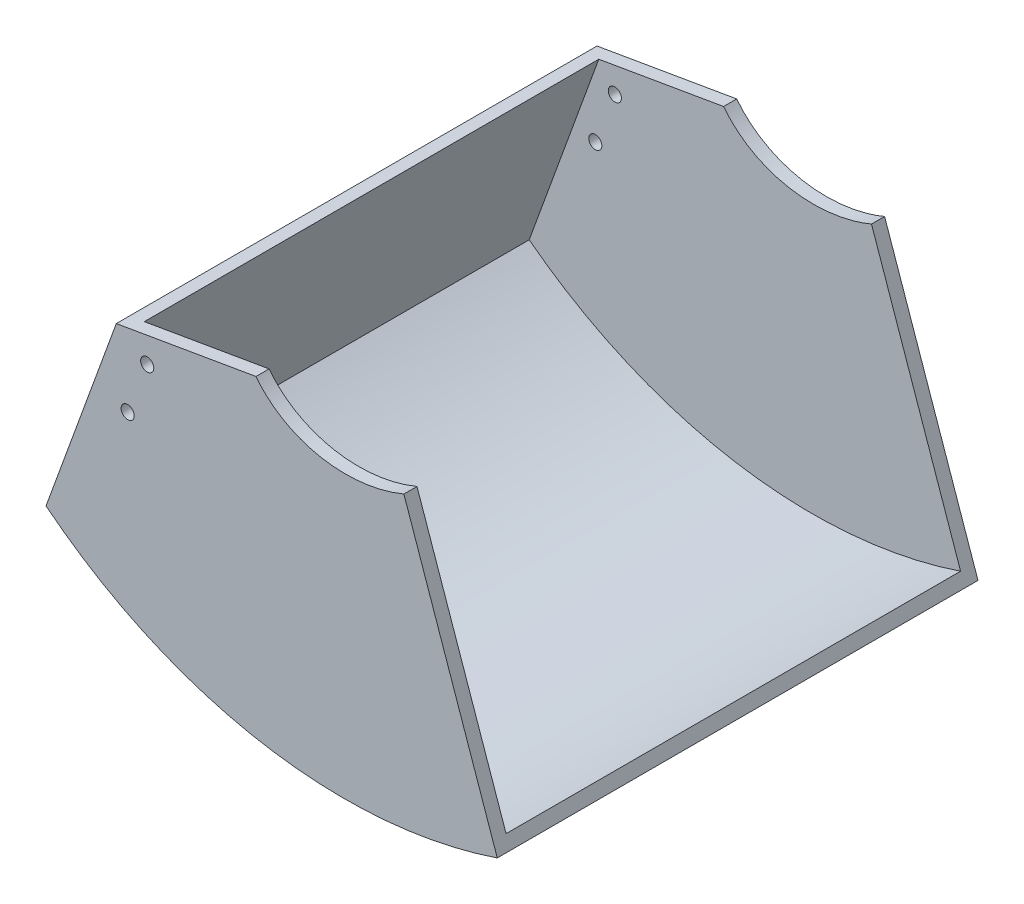
SolidWorks part; units mm, degrees
ref_plane "前视基准面" through (0, 0, 0) normal (0, 0, 1) x (1, 0, 0)
ref_plane "上视基准面" through (0, 0, 0) normal (0, 1, 0) x (1, 0, 0)
ref_plane "右视基准面" through (0, 0, 0) normal (1, 0, 0) x (0, 0, -1)
ref_plane "基准面4" through (0, 0, 110) normal (0, 0, 1) x (1, 0, 0)
sketch "草图1" plane through (0, 0, 110) normal (0, 0, 1) x (1, 0, 0)
  line L0 (48.0437, 49.6866) -> (16.0836, 44.1894)
  line L1 (16.0836, 44.1894) -> (0, 0)
  line L2 (103.2604, -18.1269) -> (81.8905, 43.3117)
  arc A0 (0, 0) -> (103.2604, -18.1269) centre (68.2396, 85.5519) ccw
  ellipse E0 centre (72.334, 64.9069) end of major axis (99.4801, 74.9971) minor radius 23.6005 (48.0437, 49.6866) -> (81.8905, 43.3117) ccw
  point P0 (72.334, 64.9069)
  point P1 (99.4801, 74.9971)
  point P2 (80.5567, 42.7851)
  point P3 (48.0437, 49.6866)
  point P4 (81.8905, 43.3117)
  point P5 (63.8108, 40.9481)
  point P6 (80.8573, 88.8657)
extrude "凸台-拉伸1" add sketch "草图1" against normal blind 3
sketch "草图2" plane through (0, 0, 107) normal (0, 0, -1) x (-1, 0, 0)
  line L0 (-3.5645, 1.022) -> (-19.4894, 44.7752)
  line L1 (-19.4894, 44.7752) -> (-16.0836, 44.1894)
  line L2 (-16.0836, 44.1894) -> (0, 0)
  line L3 (-103.2604, -18.1269) -> (-102.2748, -15.2933)
  arc A0 (-102.2748, -15.2933) -> (-3.5645, 1.022) centre (-68.2396, 85.5519) ccw
  arc A1 (0, 0) -> (-103.2604, -18.1269) centre (-68.2396, 85.5519) cw
extrude "凸台-拉伸2" add sketch "草图2" along normal blind 104
sketch "草图3" plane through (0, 0, 3) normal (0, 0, -1) x (-1, 0, 0)
  line L0 (-77.8877, 54.8198) -> (-16.0836, 44.1894)
  line L1 (-16.0836, 44.1894) -> (0, 0)
  line L2 (-103.2604, -18.1269) -> (-77.8877, 54.8198)
  arc A0 (0, 0) -> (-103.2604, -18.1269) centre (-68.2396, 85.5519) cw
extrude "凸台-拉伸3" add sketch "草图3" along normal blind 3
sketch "草图4" plane through (0, 0, 3) normal (0, 0, 1) x (1, 0, 0)
  line L0 (77.8877, 54.8198) -> (48.0437, 49.6866)
  line L1 (81.8905, 43.3117) -> (77.8877, 54.8198)
  ellipse E0 centre (72.3364, 64.9152) end of major axis (99.4836, 75.0184) minor radius 23.6075 (48.0437, 49.6866) -> (81.8905, 43.3117) ccw
  point P2 (72.3364, 64.9152)
  point P3 (99.4836, 75.0184)
  point P4 (80.5704, 42.7902)
  point P5 (48.0437, 49.6866)
  point P6 (81.8905, 43.3117)
  point P7 (63.8372, 40.9441)
  point P8 (80.8356, 88.8863)
extrude "切除-拉伸1" cut sketch "草图4" against normal through all
hole_wizard "Ø3.0 (3) 直径孔1" positions "草图6" profile "草图5" hole size "Ø3.0" standard "ANSI Metric"
sketch "草图6" plane through (0, 0, 107) normal (0, 0, -1) x (-1, 0, 0)
  point P0 (-18.6883, 27.9551)
  point P1 (-23.1583, 39.6285)
sketch "草图5" plane through (18.6883, 27.9551, 107) normal (1, 0, 0) x (0, 1, 0)
  line L0 (0, 0) -> (0, 3)
  line L1 (0, 3) -> (1.5, 3)
  line L2 (1.5, 3) -> (1.5, 0)
  line L5 (1.5, 0) -> (0, 0)
  line L11 (0, -6.35) -> (0, 107.95) construction
  dimension "通孔孔直径" = 3
  dimension "通孔孔深度" = 3
hole_wizard "Ø3.0 (3) 直径孔2" positions "草图8" profile "草图7" hole size "Ø3.0" standard "ANSI Metric"
sketch "草图8" plane through (0, 0, 0) normal (0, 0, -1) x (-1, 0, 0)
  point P0 (-18.6883, 27.9551)
  point P1 (-23.1583, 39.6285)
sketch "草图7" plane through (18.6883, 27.9551, 0) normal (1, 0, 0) x (0, 1, 0)
  line L0 (0, 0) -> (0, 110)
  line L1 (0, 110) -> (1.5, 110)
  line L2 (1.5, 110) -> (1.5, 0)
  line L5 (1.5, 0) -> (0, 0)
  line L11 (0, -6.35) -> (0, 107.95) construction
  dimension "通孔孔直径" = 3
  dimension "通孔孔深度" = 110
ref_plane "基准面5" through (0, 0, 0) normal (0, 0, -1) x (-1, 0, 0)
sketch "草图13" plane through (0, 0, 0) normal (0, 0, -1) x (-1, 0, 0)
  line L0 (-113.425, -17.6005) -> (-103.2604, -18.1269)
  arc A0 (-113.425, -17.6005) -> (-78.5064, -23.3993) centre (-77.3271, 91.7376) ccw
  spline S0 degree 3 poles (-103.2604, -18.1269) (-103.0815, -18.1871) (-102.8334, -18.2705) (-102.4543, -18.3959) (-102.2041, -18.4779) (-101.9383, -18.5643) (-101.7377, -18.629) (-98.062, -19.8061) (-90.4045, -21.8901) (-82.6174, -22.8778) (-78.5064, -23.3993) knots 0 0 0 0 0.022342 0.030962 0.047244 0.0535 0.06403 0.072187 0.510181 1 1 1 1
